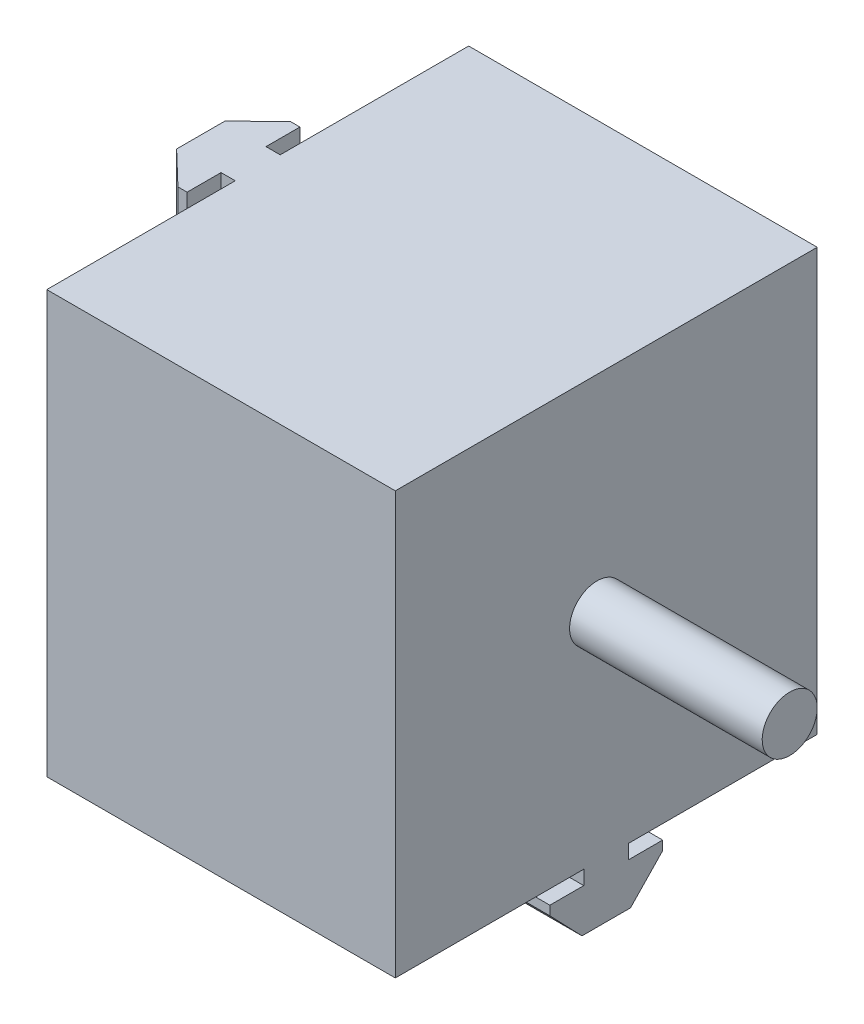
SolidWorks part; units mm, degrees
other "Marquage1"
sketch "Esquisse7" plane through (-22.1, 26.1, 52.2) normal (-0.1348, 0.2678, 0.954) x (-0.088, -0.9622, 0.2577)
ref_plane "Plan de face" through (0, 0, 0) normal (0, 0, 1) x (1, 0, 0)
ref_plane "Plan de dessus" through (0, 0, 0) normal (0, 1, 0) x (1, 0, 0)
ref_plane "Plan de droite" through (0, 0, 0) normal (1, 0, 0) x (0, 0, -1)
sketch "Esquisse1" plane through (0, 0, 0) normal (0, 0, 1) x (1, 0, 0)
  line L1 (-22.1, 26.1) -> (22.1, 26.1)
  line L2 (-22.1, 26.1) -> (-22.1, -26.1)
  line L3 (-22.1, -26.1) -> (22.1, -26.1)
  line L4 (22.1, 26.1) -> (22.1, -26.1)
  line L5 (-22.1, 26.1) -> (22.1, -26.1) construction
  line L6 (-22.1, -26.1) -> (22.1, 26.1) construction
  point P0 (0, 0)
  dimension "D1" = 44.2
  dimension "D2" = 52.2
extrude "Boss.-Extru.1" add sketch "Esquisse1" along normal blind 52.2
sketch "Esquisse2" plane through (22.1, 0, 0) normal (1, 0, 0) x (0, 0, -1)
  line L0 (-52.2, -19.9) -> (-28.55, -19.9)
  line L1 (-52.2, -26.1) -> (-52.2, 26.1) construction
  line L2 (-28.55, -19.9) -> (-28.55, -21.45)
  line L3 (-28.55, -21.45) -> (-32.25, -21.45)
  line L4 (-32.25, -21.45) -> (-32.25, -22.45)
  line L5 (-32.25, -22.45) -> (-28.7456, -26.1)
  line L6 (-52.2, -26.1) -> (0, -26.1) construction
  dimension "D1" = 23.65
  dimension "D2" = 6.2
  dimension "D3" = 1.55
  dimension "D4" = 3.7
  dimension "D5" = 1
  dimension "D6" = 5.06
extrude "Enlèv. mat.-Extru.2" cut sketch "Esquisse2" against normal blind 44.2 and the other way through all flip side to cut
sketch "Esquisse3" plane through (22.1, 0, 0) normal (1, 0, 0) x (0, 0, -1)
  line L0 (0, -19.9) -> (-23.65, -19.9)
  line L1 (0, -26.1) -> (0, 26.1) construction
  line L2 (-23.65, -19.9) -> (-23.65, -21.45)
  line L3 (-23.65, -21.45) -> (-19.95, -21.45)
  line L4 (-19.95, -21.45) -> (-19.95, -22.45)
  line L5 (-19.95, -22.45) -> (-23.4544, -26.1)
  line L6 (-28.7456, -26.1) -> (0, -26.1) construction
  dimension "D1" = 6.2
  dimension "D2" = 23.65
  dimension "D3" = 1.55
  dimension "D4" = 3.7
  dimension "D5" = 1
  dimension "D6" = 5.06
extrude "Enlèv. mat.-Extru.3" cut sketch "Esquisse3" against normal blind 44.2 and the other way through all
sketch "Esquisse4" plane through (0, 26.1, 0) normal (0, 1, 0) x (1, 0, 0)
  line L0 (-15.9, -52.2) -> (-15.9, -28.55)
  line L1 (22.1, -52.2) -> (-22.1, -52.2) construction
  line L2 (-15.9, -28.55) -> (-17.45, -28.55)
  line L3 (-17.45, -28.55) -> (-17.45, -32.25)
  line L4 (-17.45, -32.25) -> (-18.45, -32.25)
  line L5 (-18.45, -32.25) -> (-22.1, -28.7456)
  line L6 (-22.1, -52.2) -> (-22.1, 0) construction
  dimension "D1" = 6.2
  dimension "D2" = 23.65
  dimension "D3" = 1.55
  dimension "D4" = 3.7
  dimension "D5" = 1
  dimension "D6" = 5.06
extrude "Enlèv. mat.-Extru.4" cut sketch "Esquisse4" against normal blind 46 and the other way through all
sketch "Esquisse5" plane through (0, 26.1, 0) normal (0, 1, 0) x (1, 0, 0)
  line L0 (-15.9, 0) -> (-15.9, -23.65)
  line L1 (22.1, 0) -> (-22.1, 0) construction
  line L2 (-15.9, -23.65) -> (-17.45, -23.65)
  line L3 (-17.45, -23.65) -> (-17.45, -19.95)
  line L4 (-17.45, -19.95) -> (-18.45, -19.95)
  line L5 (-18.45, -19.95) -> (-22.1, -23.4544)
  line L6 (-22.1, -28.7456) -> (-22.1, 0) construction
  dimension "D1" = 6.2
  dimension "D2" = 23.65
  dimension "D3" = 1.55
  dimension "D4" = 3.7
  dimension "D5" = 1
  dimension "D6" = 5.06
extrude "Enlèv. mat.-Extru.5" cut sketch "Esquisse5" against normal blind 46 and the other way through all flip side to cut
sketch "Esquisse6" plane through (0, 0, 28.55) normal (0, 0, 1) x (1, 0, 0)
  line L0 (-22.1, -19.9) -> (-15.9, -19.9)
  line L1 (-15.9, -19.9) -> (-15.9, -26.0936)
extrude "Enlèv. mat.-Extru.7" cut sketch "Esquisse6" against normal through all both and the other way through all flip side to cut
sketch "Esquisse11" plane through (0, 26.1, 0) normal (0, 1, 0) x (1, 0, 0)
  line L0 (22.1, -52.2) -> (22.1, 0) construction
  line L1 (22.1, -49.1) -> (-15.9, -49.1)
  line L2 (-15.9, -28.55) -> (-15.9, -52.2) construction
  line L3 (22.1, -52.2) -> (-15.9, -52.2) construction
  dimension "D1" = 3.1
extrude "Enlèv. mat.-Extru.8" cut sketch "Esquisse11" against normal blind 46 and the other way through all
sketch "Esquisse12" plane through (0, 26.1, 0) normal (0, 1, 0) x (1, 0, 0)
  line L0 (22.1, -49.1) -> (22.1, 0) construction
  line L1 (22.1, -3.1) -> (-15.9, -3.1)
  line L2 (-15.9, -23.65) -> (-15.9, 0) construction
  line L3 (22.1, 0) -> (-15.9, 0) construction
  dimension "D1" = 3.1
extrude "Enlèv. mat.-Extru.9" cut sketch "Esquisse12" against normal blind 46 and the other way through all flip side to cut
sketch "Esquisse13" plane through (22.1, 0, 0) normal (1, 0, 0) x (0, 0, -1)
  line L0 (-28.55, -19.9) -> (-49.1, -19.9) construction
  line L1 (-3.1, 26.1) -> (-3.1, -19.9) construction
  circle A0 centre (-27.1, 3.6) radius 3
  dimension "D1" = 23.5
  dimension "D2" = 24
extrude "Boss.-Extru.2" add sketch "Esquisse13" along normal blind 21
